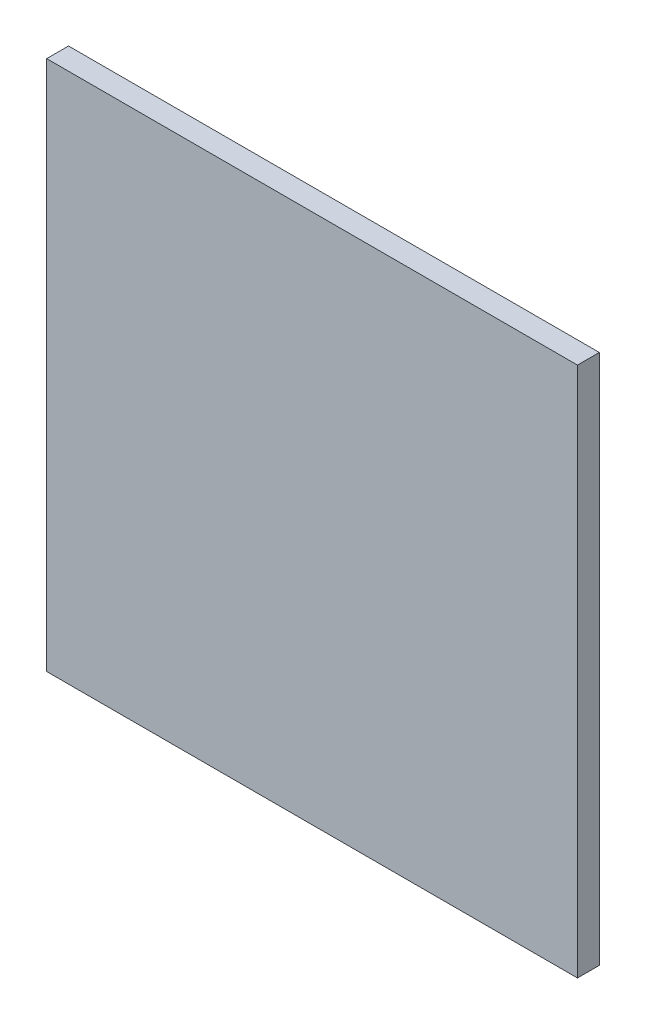
SolidWorks part; units mm, degrees
material "Сплав 2024"
ref_plane "Спереди" through (0, 0, 0) normal (0, 0, 1) x (1, 0, 0)
ref_plane "Сверху" through (0, 0, 0) normal (0, 1, 0) x (1, 0, 0)
ref_plane "Справа" through (0, 0, 0) normal (1, 0, 0) x (0, 0, -1)
sketch "Эскиз1" plane through (0, 0, 0) normal (0, 0, 1) x (1, 0, 0)
  line L1 (-170, 170) -> (170, 170)
  line L2 (-170, 170) -> (-170, -170)
  line L3 (-170, -170) -> (170, -170)
  line L4 (170, 170) -> (170, -170)
  line L5 (-170, 170) -> (170, -170) construction
  line L6 (-170, -170) -> (170, 170) construction
  point P0 (0, 0)
  dimension "D1" = 340
  dimension "D2" = 340
extrude "Бобышка-Вытянуть1" add sketch "Эскиз1" along normal blind 14
